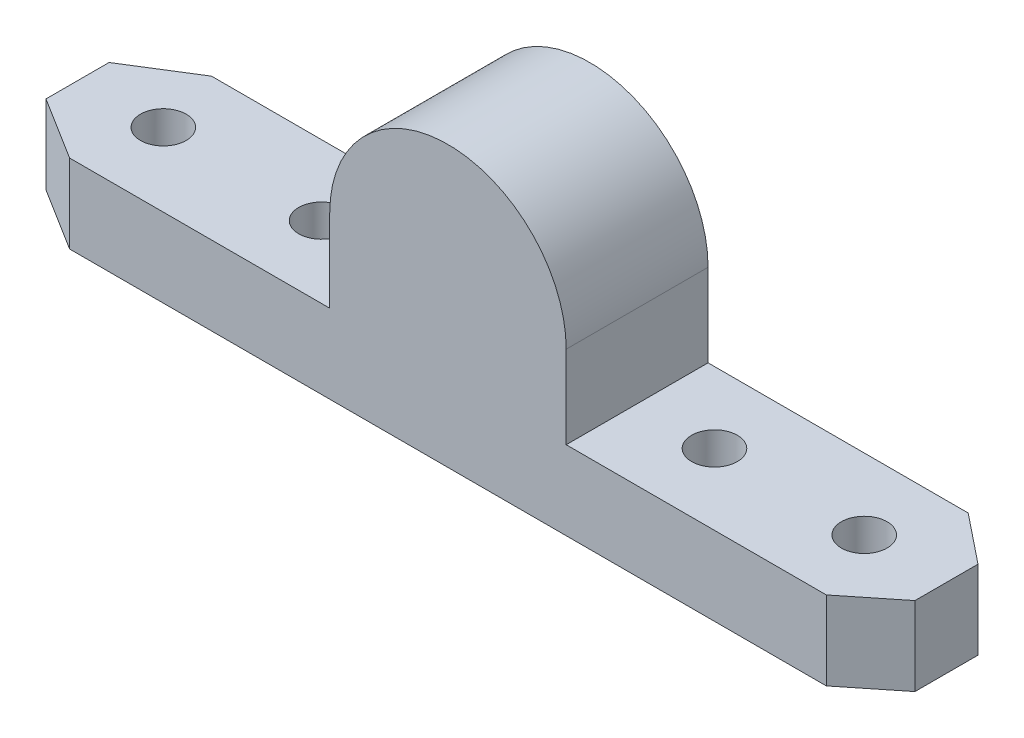
SolidWorks part; units mm, degrees
ref_plane "Płaszczyzna przednia" through (0, 0, 0) normal (0, 0, 1) x (1, 0, 0)
ref_plane "Płaszczyzna górna" through (0, 0, 0) normal (0, 1, 0) x (1, 0, 0)
ref_plane "Płaszczyzna prawa" through (0, 0, 0) normal (1, 0, 0) x (0, 0, -1)
sketch "Szkic1" plane through (0, 0, 0) normal (0, 1, 0) x (1, 0, 0)
  line L0 (24, 4.5) -> (27.1225, 2)
  line L1 (27.1225, 2) -> (27.1225, -2)
  line L2 (-24, -4.5) -> (24, -4.5)
  line L4 (-24, 4.5) -> (24, 4.5)
  line L6 (-24, -4.5) -> (24, 4.5) construction
  line L7 (-24, 4.5) -> (24, -4.5) construction
  line L8 (27.1225, -2) -> (24, -4.5)
  line L9 (-24, 4.5) -> (-28, 2)
  line L10 (-28, 2) -> (-28, -2)
  line L11 (-28, -2) -> (-24, -4.5)
  point P1 (0, 0)
  dimension "D3" = 4
  dimension "D1" = 48
  dimension "D2" = 9
  dimension "D4" = 4
  dimension "D5" = 4
  dimension "D6" = 4
  dimension "D7" = 4
  dimension "D8" = 4
extrude "Dodanie-wyciągnięcie1" add sketch "Szkic1" along normal blind 5
sketch "Szkic2" plane through (0, 0, 4.5) normal (0, 0, 1) x (1, 0, 0)
  line L0 (-24, 5) -> (24, 5) construction
  line L1 (-7.5, 5) -> (7.5, 5)
  line L2 (-7.5, 5) -> (-7.5, 10.25)
  line L4 (7.5, 10.25) -> (7.5, 5)
  arc A0 (-7.5, 10.25) -> (7.5, 10.25) centre (0, 10.25) cw
  point P7 (0, 5)
  dimension "D3" = 7.5
  dimension "D1" = 15
  dimension "D2" = 5.25
extrude "Dodanie-wyciągnięcie2" add sketch "Szkic2" against normal blind 9
sketch "Szkic3" plane through (0, 0, 4.5) normal (0, 0, 1) x (1, 0, 0)
  line L0 (0, 0) -> (0, 11) construction
  line L1 (-24, 0) -> (24, 0) construction
  circle A0 centre (0, 11) radius 3
  dimension "D2" = 6
  dimension "D1" = 11
sketch "Szkic4" plane through (0, 5, 0) normal (0, 1, 0) x (1, 0, 0)
  line L0 (27.1225, 0) -> (7.5, 0) construction
  line L1 (27.1225, -2) -> (27.1225, 2) construction
  line L2 (7.5, 4.5) -> (7.5, -4.5) construction
  line L3 (7.5, 0) -> (17.3112, 0) construction
  line L4 (17.3112, 0) -> (12.4056, 0) construction
  line L5 (12.4056, 0) -> (21.9056, 0) construction
  line L6 (-27.7881, 0.2121) -> (-7.5, 0) construction
  line L7 (-7.5, 4.5) -> (-7.5, -4.5) construction
  line L8 (-7.5, 0) -> (-17.644, 0.1061) construction
  line L9 (-17.644, 0.1061) -> (-12.572, 0.053) construction
  line L10 (-27.7881, 0.2121) -> (-17.644, 0.1061) construction
  line L11 (-17.644, 0.1061) -> (-22.716, 0.1591) construction
  circle A0 centre (12.4056, 0) radius 1.45
  circle A1 centre (21.9056, 0) radius 1.45
  circle A2 centre (-12.572, 0.053) radius 1.45
  circle A3 centre (-22.716, 0.1591) radius 1.45
  dimension "D1" = 2.9
  dimension "D3" = 2.9
  dimension "D4" = 2.9
  dimension "D5" = 2.9
  dimension "D2" = 9.5
extrude "Wytnij-wyciągnięcie1" cut sketch "Szkic4" against normal blind 6
